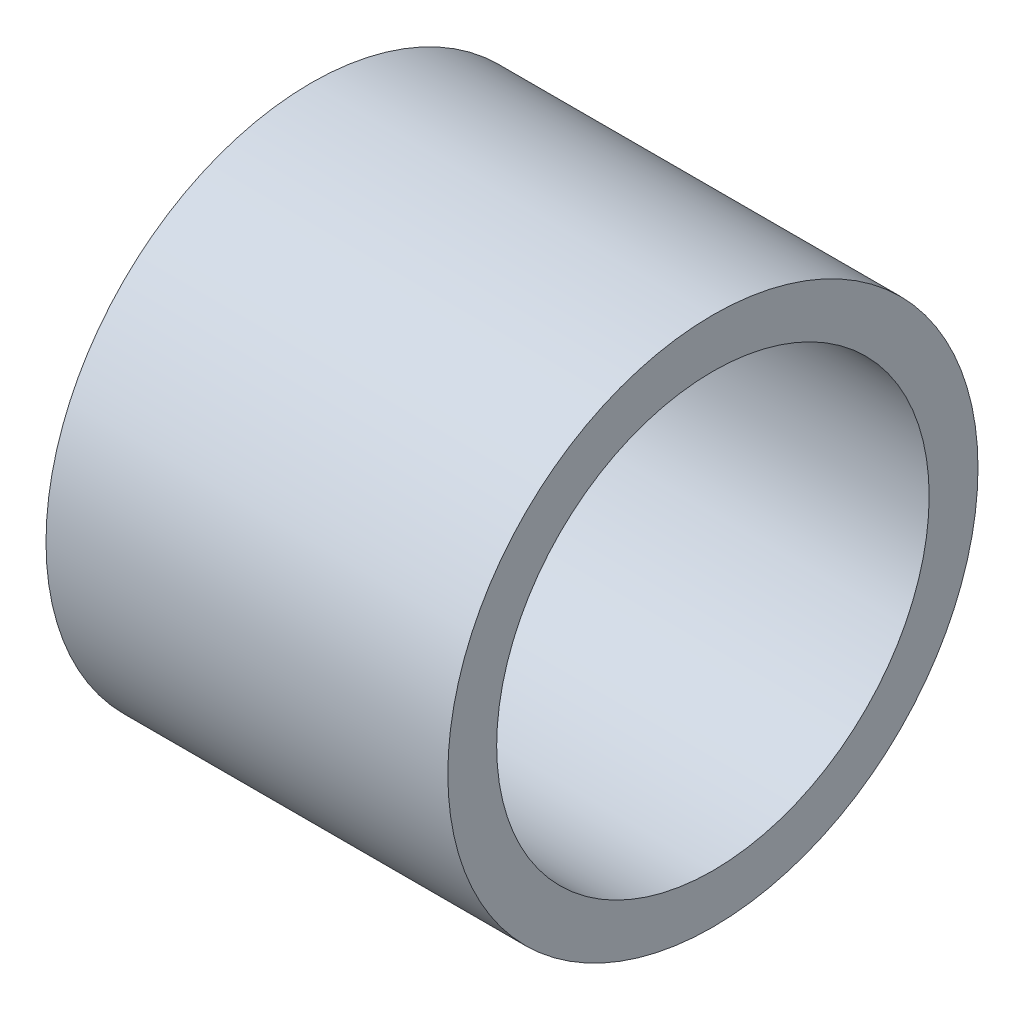
SolidWorks part; units mm, degrees
material "PUR"
ref_plane "Front" through (0, 0, 0) normal (0, 0, 1) x (1, 0, 0)
ref_plane "Top" through (0, 0, 0) normal (0, 1, 0) x (1, 0, 0)
ref_plane "Right" through (0, 0, 0) normal (1, 0, 0) x (0, 0, -1)
sketch "Sketch1" plane through (0, 0, 0) normal (1, 0, 0) x (0, 0, -1)
  circle A0 centre (0, 0) radius 7.75
  circle A1 centre (0, 0) radius 9.5
  dimension "D1" = 19
  dimension "D2" = 15.5
extrude "Boss-Extrude1" add sketch "Sketch1" along normal mid plane 14.4
